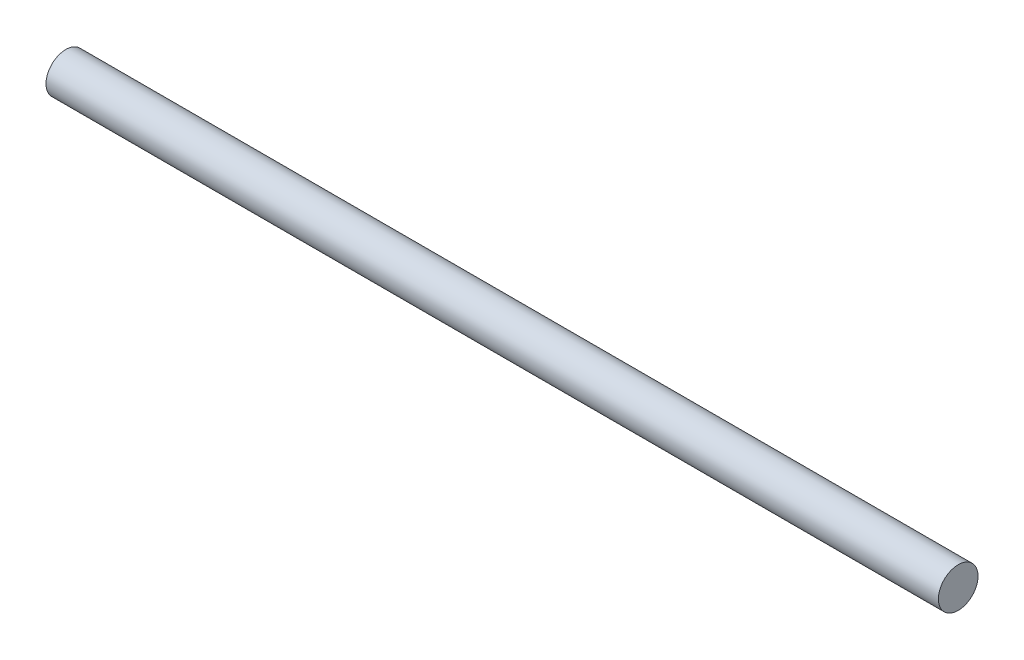
SolidWorks part; units mm, degrees
ref_plane "前视基准面" through (0, 0, 0) normal (0, 0, 1) x (1, 0, 0)
ref_plane "上视基准面" through (0, 0, 0) normal (0, 1, 0) x (1, 0, 0)
ref_plane "右视基准面" through (0, 0, 0) normal (1, 0, 0) x (0, 0, -1)
ref_plane "基准面4" through (0, 0, 5) normal (0, 0, -1) x (-1, 0, 0)
sketch "草图1" plane through (0, 0, 5) normal (0, 0, -1) x (-1, 0, 0)
  line L0 (-45, -73) -> (-45, -75)
  line L1 (-45, -75) -> (45, -75)
  line L2 (45, -75) -> (45, -73)
  line L3 (45, -73) -> (-45, -73)
  line L4 (-45, -75) -> (45, -75) construction
revolve "旋转1" add sketch "草图1" angle 360 about L4
